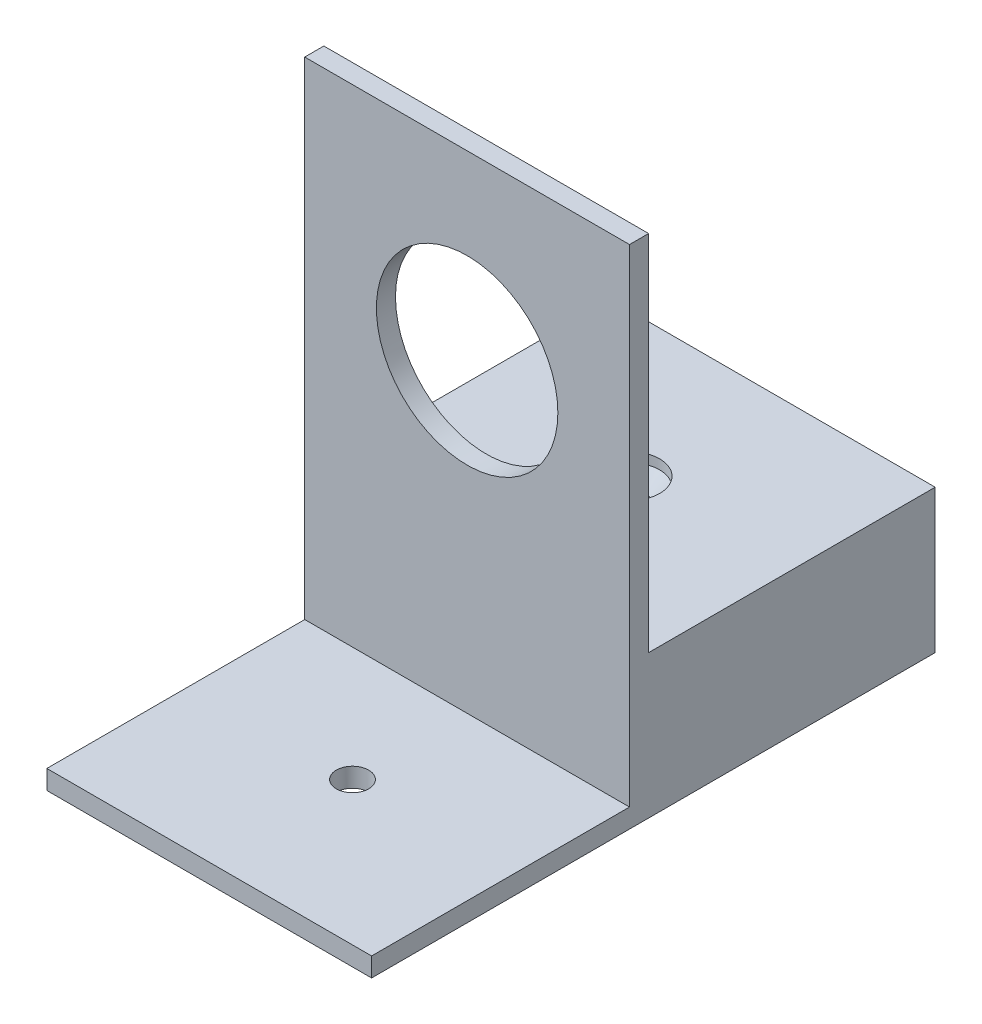
SolidWorks part; units mm, degrees
ref_plane "Front" through (0, 0, 0) normal (0, 0, 1) x (1, 0, 0)
ref_plane "Top" through (0, 0, 0) normal (0, 1, 0) x (1, 0, 0)
ref_plane "Right" through (0, 0, 0) normal (1, 0, 0) x (0, 0, -1)
sketch "Sketch1" plane through (0, 0, 0) normal (0, 0, 1) x (1, 0, 0)
  line L1 (0, 0) -> (34, 0)
  line L2 (0, 0) -> (0, 53)
  line L3 (0, 53) -> (34, 53)
  line L4 (34, 0) -> (34, 53)
  dimension "D1" = 53
  dimension "D2" = 34
extrude "Boss-Extrude1" add sketch "Sketch1" along normal blind 2
sketch "Sketch2" plane through (0, 0, 2) normal (0, 0, 1) x (1, 0, 0)
  line L0 (34, 0) -> (34, 53) construction
  line L1 (0, 0) -> (34, 0)
  line L2 (0, 0) -> (0, 2)
  line L3 (0, 2) -> (34, 2)
  line L4 (34, 0) -> (34, 2)
  dimension "D1" = 2
extrude "Boss-Extrude2" add sketch "Sketch2" along normal blind 27
sketch "Sketch3" plane through (0, 0, 0) normal (0, 0, -1) x (-1, 0, 0)
  line L0 (-34, 0) -> (-34, 53) construction
  line L1 (0, 0) -> (-34, 0)
  line L2 (0, 0) -> (0, 15)
  line L3 (0, 15) -> (-34, 15)
  line L4 (-34, 0) -> (-34, 15)
  dimension "D1" = 15
extrude "Boss-Extrude3" add sketch "Sketch3" along normal blind 30
sketch "Sketch4" plane through (0, 0, 2) normal (0, 0, 1) x (1, 0, 0)
  line L0 (17, -5.9529) -> (17, 59.0578) construction
  line L1 (0, 53) -> (0, 2) construction
  line L2 (34, 53) -> (0, 53) construction
  circle A0 centre (17, 34) radius 9.5
  dimension "D2" = 19
  dimension "D1" = 17
  dimension "D3" = 19
extrude "Cut-Extrude1" cut sketch "Sketch4" against normal through all contours A0
sketch "Sketch6" plane through (0, 0, 0) normal (0, -1, 0) x (-1, 0, 0)
  line L0 (-17, -29) -> (-17, 30) construction
  line L1 (0, -29) -> (-34, -29) construction
  line L2 (-34, 30) -> (0, 30) construction
hole_wizard "CSK for M3 Flat Head Machine Screw1" positions "Sketch12" profile "Sketch9" countersink size "M3" standard "ANSI Metric" end condition through all
sketch "Sketch12" plane through (0, 15, 0) normal (0, 1, 0) x (1, 0, 0)
  line L0 (17, -29) -> (17, 30) construction
  point P0 (17, 15)
  point P4 (17, -14)
  dimension "D1" = 15
  dimension "D2" = 15
sketch "Sketch9" plane through (17, 15, -15) normal (1, 0, 0) x (0, 0, 1)
  line L0 (0, 0) -> (0, 15)
  line L1 (0, 15) -> (1.7, 15)
  line L2 (1.7, 15) -> (1.7, 2.45)
  line L3 (1.7, 2.45) -> (3.15, 1)
  line L4 (3.15, 1) -> (3.15, 0)
  line L6 (3.15, 0) -> (0, 0)
  line L7 (-1.7, 2.45) -> (-3.15, 1) construction
  line L11 (0, -6.35) -> (0, 107.95) construction
  dimension "Thru Hole Dia." = 3.4
  dimension "Thru Hole Depth" = 15
  dimension "C'Sink Dia." = 6.3
  dimension "C'Sink Angle" = 90
  dimension "Head Clearance" = 1
